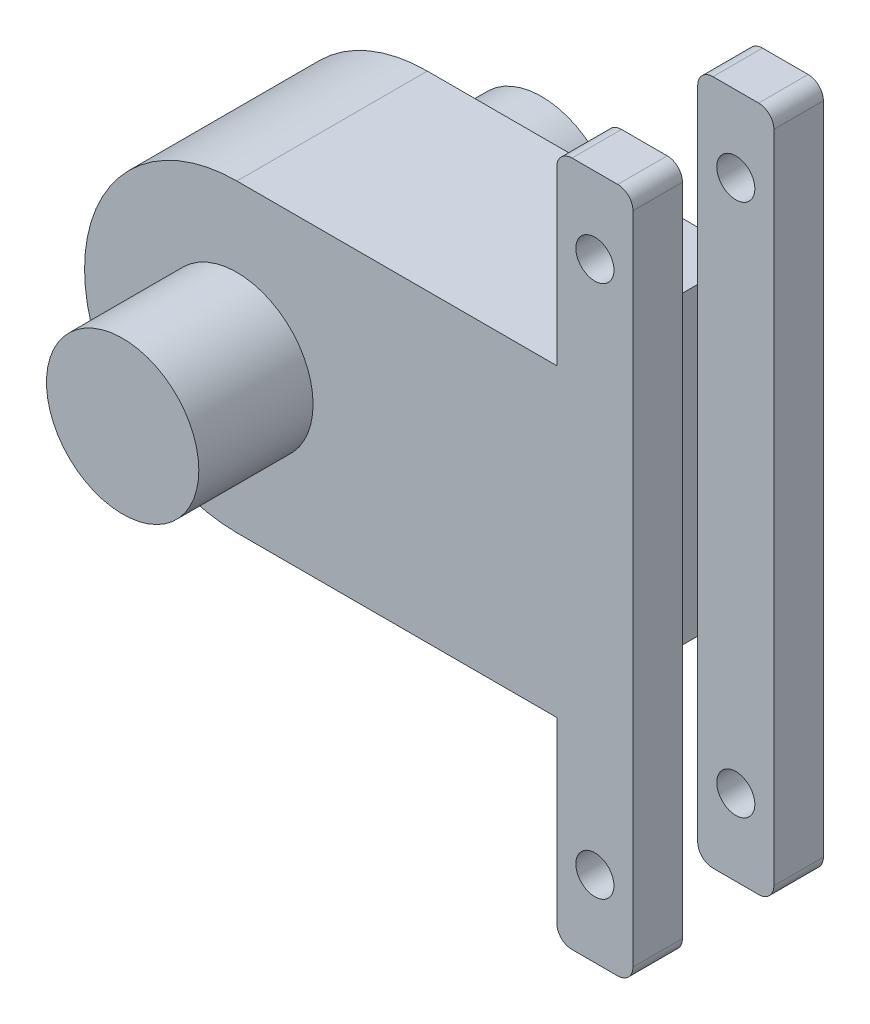
SolidWorks part; units mm, degrees
ref_plane "Front Plane" through (0, 0, 0) normal (0, 0, 1) x (1, 0, 0)
ref_plane "Top Plane" through (0, 0, 0) normal (0, 1, 0) x (1, 0, 0)
ref_plane "Right Plane" through (0, 0, 0) normal (1, 0, 0) x (0, 0, -1)
sketch "Sketch1" plane through (0, 0, 0) normal (0, 0, 1) x (1, 0, 0)
  line L0 (19.9963, 0) -> (42, 0) construction
  line L1 (42, -45) -> (42, -19.6169)
  line L2 (42, 45) -> (52, 45)
  line L3 (52, 45) -> (52, -45)
  line L4 (52, -45) -> (42, -45)
  line L5 (0, 20.3831) -> (42, 20.3831)
  line L6 (0, -19.6169) -> (42, -19.6169)
  line L7 (42, 20.3831) -> (42, 45)
  arc A0 (0, 20.3831) -> (0, -19.6169) centre (0, 0.3831) ccw
  circle A1 centre (47, 35) radius 2.5
  circle A2 centre (47, -35) radius 2.5
  point P8 (42, 0)
  dimension "D2" = 40
  dimension "D1" = 5
  dimension "D3" = 90
  dimension "D4" = 10
  dimension "D5" = 10
extrude "Boss-Extrude1" add sketch "Sketch1" along normal blind 25
sketch "Sketch2" plane through (0, 0, 25) normal (0, 0, 1) x (1, 0, 0)
  circle A0 centre (0, 0) radius 10
  dimension "D1" = 20
extrude "Boss-Extrude2" add sketch "Sketch2" along normal blind 15
ref_plane "Plane1" through (0, 0, 12.5) normal (0, 0, 1) x (1, 0, 0)
mirror "Mirror1" about plane through (0, 0, 12.5) normal (0, 0, 1) of "Boss-Extrude2"
sketch "Sketch3" plane through (0, 45, 0) normal (0, 1, 0) x (1, 0, 0)
  line L0 (42, -12.5) -> (52.0157, -12.5) construction
  line L1 (42, -25) -> (42, 0) construction
  line L2 (-39.6, -12.5) -> (39.6, -12.5) construction
  line L4 (52.0157, -18.5) -> (42, -18.5)
  line L5 (52.0157, -18.5) -> (52.0157, -6.5)
  line L6 (52.0157, -6.5) -> (42, -6.5)
  line L7 (42, -18.5) -> (42, -6.5)
  line L8 (52.0157, -18.5) -> (42, -6.5) construction
  line L9 (52.0157, -6.5) -> (42, -18.5) construction
  point P6 (47.0079, -12.5)
  dimension "D1" = 12
extrude "Cut-Extrude1" cut sketch "Sketch3" against normal through all and the other way through all
fillet "Fillet2" radius 2 8 edges at (42, 45, 21.75) (42, 45, 3.25) (52, 45, 3.25) (52, 45, 21.75) (42, -45, 21.75) (42, -45, 3.25) (52, -45, 21.75) (52, -45, 3.25)
